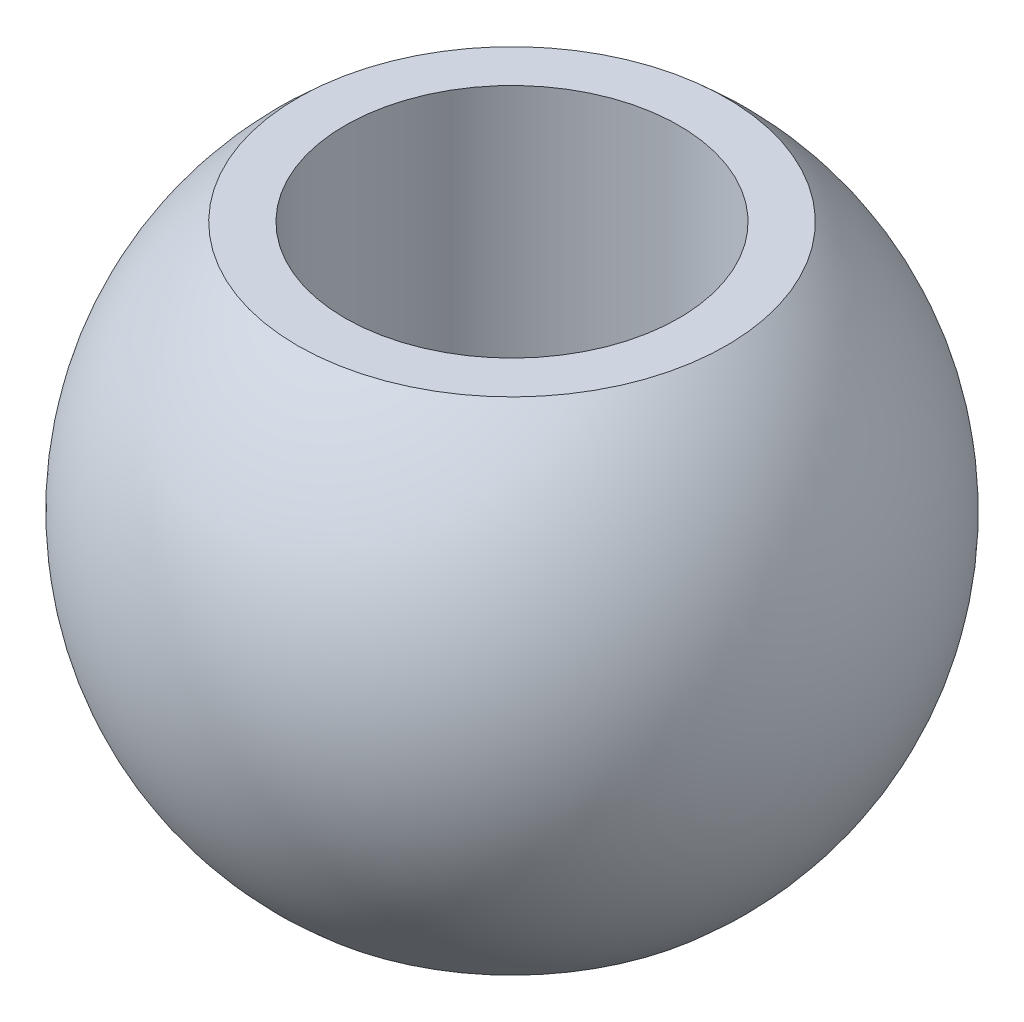
SolidWorks part; units mm, degrees
ref_plane "Front Plane" through (0, 0, 0) normal (0, 0, 1) x (1, 0, 0)
ref_plane "Top Plane" through (0, 0, 0) normal (0, 1, 0) x (1, 0, 0)
ref_plane "Right Plane" through (0, 0, 0) normal (1, 0, 0) x (0, 0, -1)
sketch "Sketch1" plane through (0, 0, 0) normal (0, 1, 0) x (1, 0, 0)
  line L0 (-7.9, 0) -> (7.9, 0)
  arc A0 (7.9, 0) -> (-7.9, 0) centre (0, 0) ccw
  dimension "D1" = 15.8
revolve "Revolve1" add sketch "Sketch1" angle 360 about L0
sketch "Sketch2" plane through (0, 0, 0) normal (1, 0, 0) x (0, 0, -1)
  line L0 (0, 0) -> (0, 6) construction
  line L1 (0, 0) -> (0, -6) construction
  line L2 (0, 6) -> (11.0019, 6)
  line L3 (0, -6) -> (12.7022, -6)
  line L5 (11.0019, 6) -> (-10.1153, 6)
  line L6 (11.0019, 6) -> (11.0019, 8.3443)
  line L7 (11.0019, 8.3443) -> (-10.1153, 8.3443)
  line L8 (-10.1153, 6) -> (-10.1153, 8.3443)
  line L9 (12.7022, -6) -> (-10.2766, -6)
  line L10 (12.7022, -6) -> (12.7022, -8.6466)
  line L11 (12.7022, -8.6466) -> (-10.2766, -8.6466)
  line L12 (-10.2766, -6) -> (-10.2766, -8.6466)
  dimension "D1" = 6
  dimension "D2" = 6
extrude "Cut-Extrude1" cut sketch "Sketch2" against normal through all both and the other way through all contours L8 L5 L2 L6 L7 | L9 L12 L11 L10 L3
sketch "Sketch3" plane through (0, 6, 0) normal (0, 1, 0) x (1, 0, 0)
  circle A0 centre (0, 0) radius 4
  dimension "D1" = 8
extrude "Cut-Extrude2" cut sketch "Sketch3" against normal through all both
